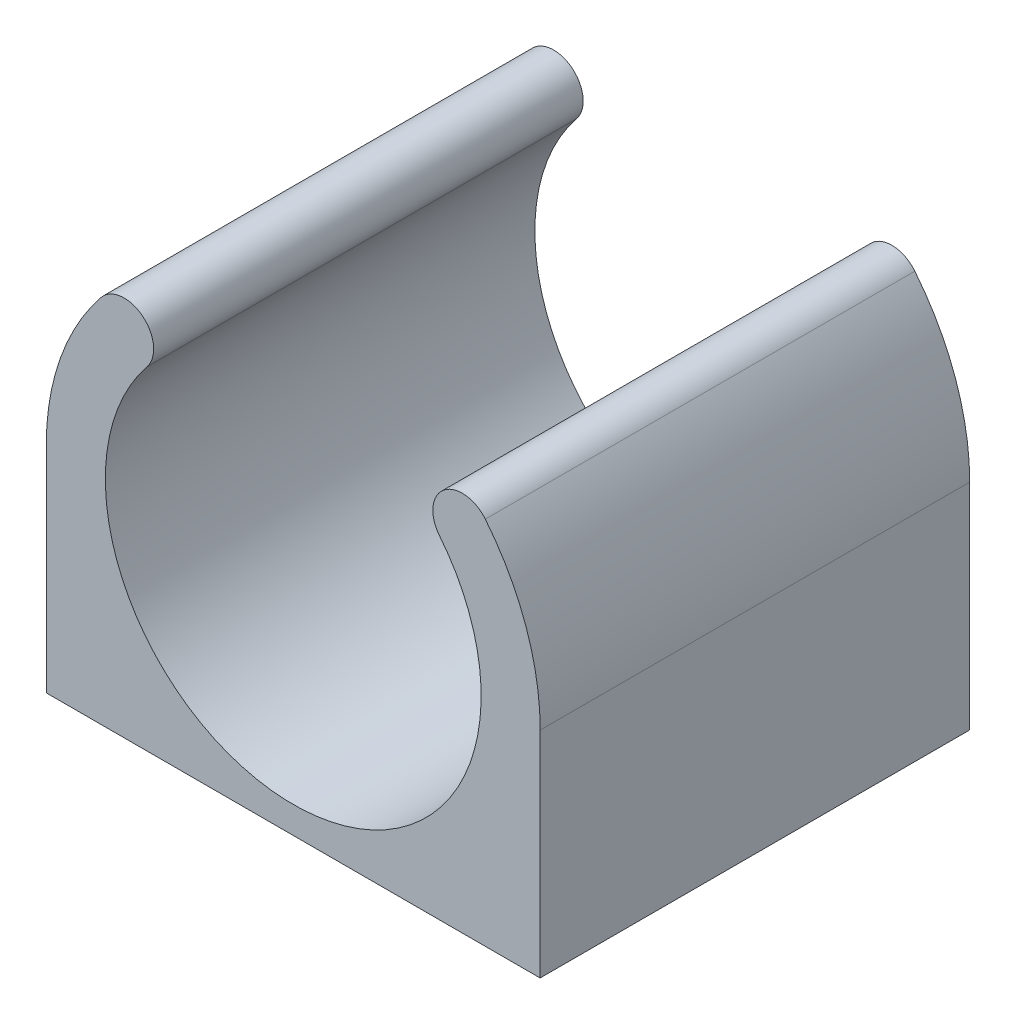
SolidWorks part; units mm, degrees
ref_plane "前视基准面" through (0, 0, 0) normal (0, 0, 1) x (1, 0, 0)
ref_plane "上视基准面" through (0, 0, 0) normal (0, 1, 0) x (1, 0, 0)
ref_plane "右视基准面" through (0, 0, 0) normal (1, 0, 0) x (0, 0, -1)
sketch "草图1" plane through (0, 0, 0) normal (0, 0, 1) x (1, 0, 0)
  line L0 (0, 0) -> (0, -2) construction
  line L1 (0, 0) -> (0, 1.1) construction
  line L2 (-1.3611, 1.1) -> (1.3611, 1.1) construction
  line L3 (0, 0) -> (-1.7888, 1.4457) construction
  line L4 (0, 0) -> (1.7888, 1.4457) construction
  line L5 (-2.2991, -2) -> (2.2991, -2)
  line L6 (-2.2991, -2) -> (-2.3, 0)
  line L7 (2.2991, -2) -> (2.3, 0)
  arc A0 (-1.3611, 1.1) -> (1.3611, 1.1) centre (0, 0) ccw
  arc A1 (-1.7888, 1.4457) -> (-2.3, 0) centre (0, 0) ccw
  arc A2 (2.3, 0) -> (1.7888, 1.4457) centre (0, 0) ccw
  arc A4 (-1.3611, 1.1) -> (-1.7888, 1.4457) centre (-1.5749, 1.2729) ccw
  arc A5 (1.3611, 1.1) -> (1.7888, 1.4457) centre (1.5749, 1.2729) cw
  point P7 (0, 1.1)
  point P11 (0, -2)
  dimension "D1" = 3.5
  dimension "D3" = 4.6
  dimension "D2" = 1.1
  dimension "D4" = 2
extrude "凸台-拉伸1" add sketch "草图1" along normal blind 4
